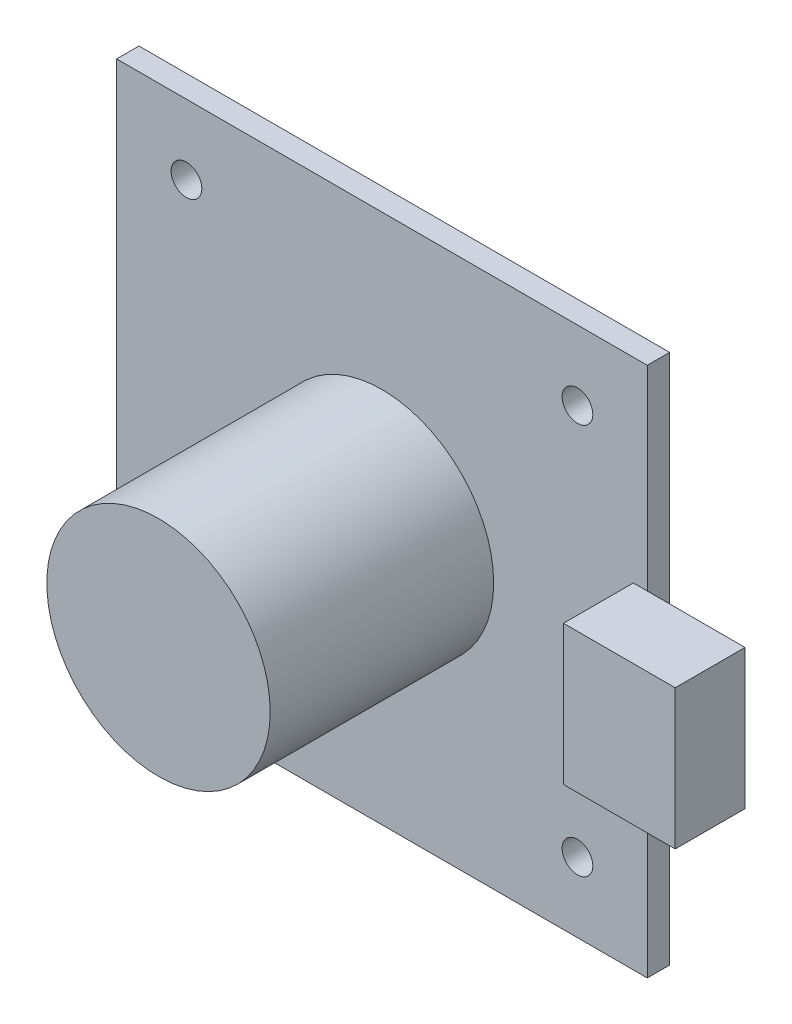
SolidWorks part; units mm, degrees
ref_plane "前视基准面" through (0, 0, 0) normal (0, 0, 1) x (1, 0, 0)
ref_plane "上视基准面" through (0, 0, 0) normal (0, 1, 0) x (1, 0, 0)
ref_plane "右视基准面" through (0, 0, 0) normal (1, 0, 0) x (0, 0, -1)
other "Configuration Table"
sketch "草图1" plane through (0, 0, 0) normal (0, 0, 1) x (1, 0, 0)
  line L0 (-19, -19) -> (19, -19)
  line L1 (19, -19) -> (19, 19)
  line L2 (19, 19) -> (-19, 19)
  line L3 (-19, 19) -> (-19, -19)
  circle A0 centre (-14, -14) radius 1.1
  circle A1 centre (-14, 14) radius 1.1
  circle A2 centre (14, -14) radius 1.1
  circle A3 centre (14, 14) radius 1.1
extrude "USB摄像头38方PCB占位" add sketch "草图1" along normal blind 1.6
sketch "草图2" plane through (0, 0, 0) normal (0, 0, 1) x (1, 0, 0)
  circle A0 centre (0, 0) radius 8
extrude "M12镜头占位" add sketch "草图2" along normal blind 16 from offset 1.6
sketch "草图3" plane through (0, 0, 0) normal (0, 0, 1) x (1, 0, 0)
  line L0 (18, -5) -> (26, -5)
  line L1 (26, -5) -> (26, 5)
  line L2 (26, 5) -> (18, 5)
  line L3 (18, 5) -> (18, -5)
extrude "USB插头接口占位" add sketch "草图3" along normal blind 5 from offset 1.6
